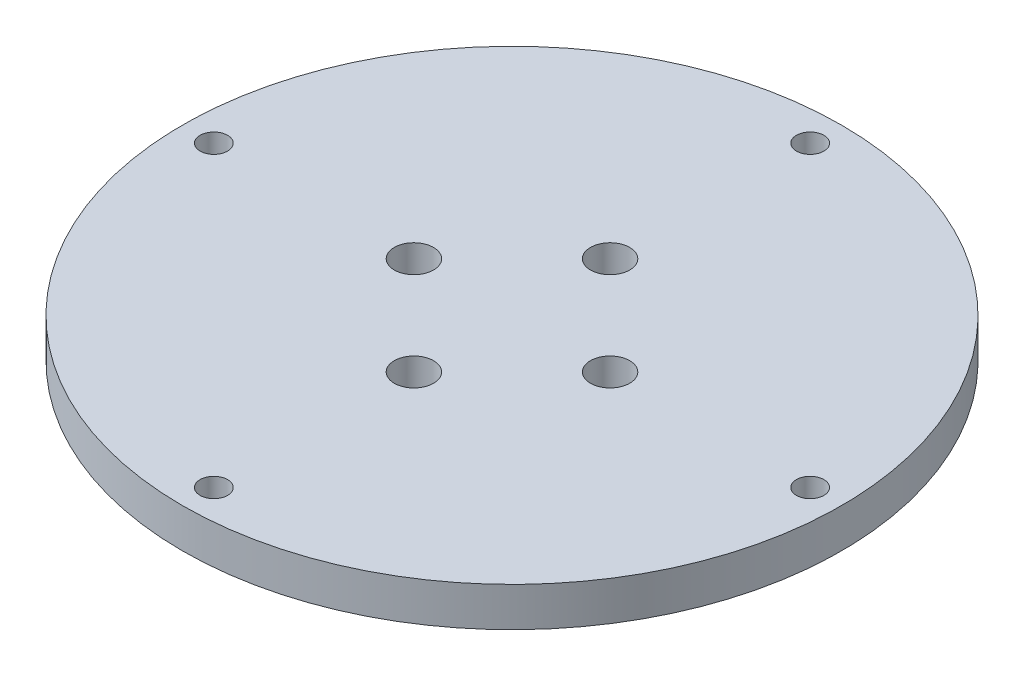
SolidWorks part; units mm, degrees
ref_plane "Front Plane" through (0, 0, 0) normal (0, 0, 1) x (1, 0, 0)
ref_plane "Top Plane" through (0, 0, 0) normal (0, 1, 0) x (1, 0, 0)
ref_plane "Right Plane" through (0, 0, 0) normal (1, 0, 0) x (0, 0, -1)
sketch "Sketch1" plane through (0, 0, 0) normal (0, 1, 0) x (1, 0, 0)
  circle A0 centre (0, 0) radius 84
  dimension "D1" = 168
extrude "Boss-Extrude1" add sketch "Sketch1" along normal blind 10
sketch "Sketch2" plane through (0, 10, 0) normal (0, 1, 0) x (1, 0, 0)
  circle A0 centre (0, 0) radius 76
  circle A1 centre (0, 76) radius 5.4022
  circle A2 centre (-76, 0) radius 2.1927
  circle A3 centre (76, 0) radius 2.6351
  circle A4 centre (0, -76) radius 3.4633
  dimension "D1" = 152
hole_wizard "M6 Clearance Hole1" positions "3DSketch1" profile "Sketch3" hole size "M6" standard "ISO" end condition through all
sketch3d "3DSketch1"
  point P0 (0, 10, -76)
  point P3 (-76, 10, 0)
  point P6 (0, 10, 76)
  point P9 (76, 10, 0)
sketch "Sketch3" plane through (0, 10, -76) normal (1, 0, 0) x (0, 0, 1)
  line L0 (0, 0) -> (0, 10)
  line L1 (0, 10) -> (3.5, 10)
  line L2 (3.5, 10) -> (3.5, 0)
  line L5 (3.5, 0) -> (0, 0)
  line L11 (0, -6.35) -> (0, 107.95) construction
  dimension "Thru Hole Dia." = 7
  dimension "Thru Hole Depth" = 10
sketch "Sketch4" plane through (0, 10, 0) normal (0, 1, 0) x (1, 0, 0)
  circle A1 centre (0, 25) radius 5
  circle A2 centre (25, 0) radius 5
  circle A3 centre (-25, 0) radius 5
  circle A4 centre (0, -25) radius 5
  dimension "D2" = 10
  dimension "D3" = 10
  dimension "D4" = 10
  dimension "D5" = 10
extrude "Cut-Extrude1" cut sketch "Sketch4" against normal blind 10
